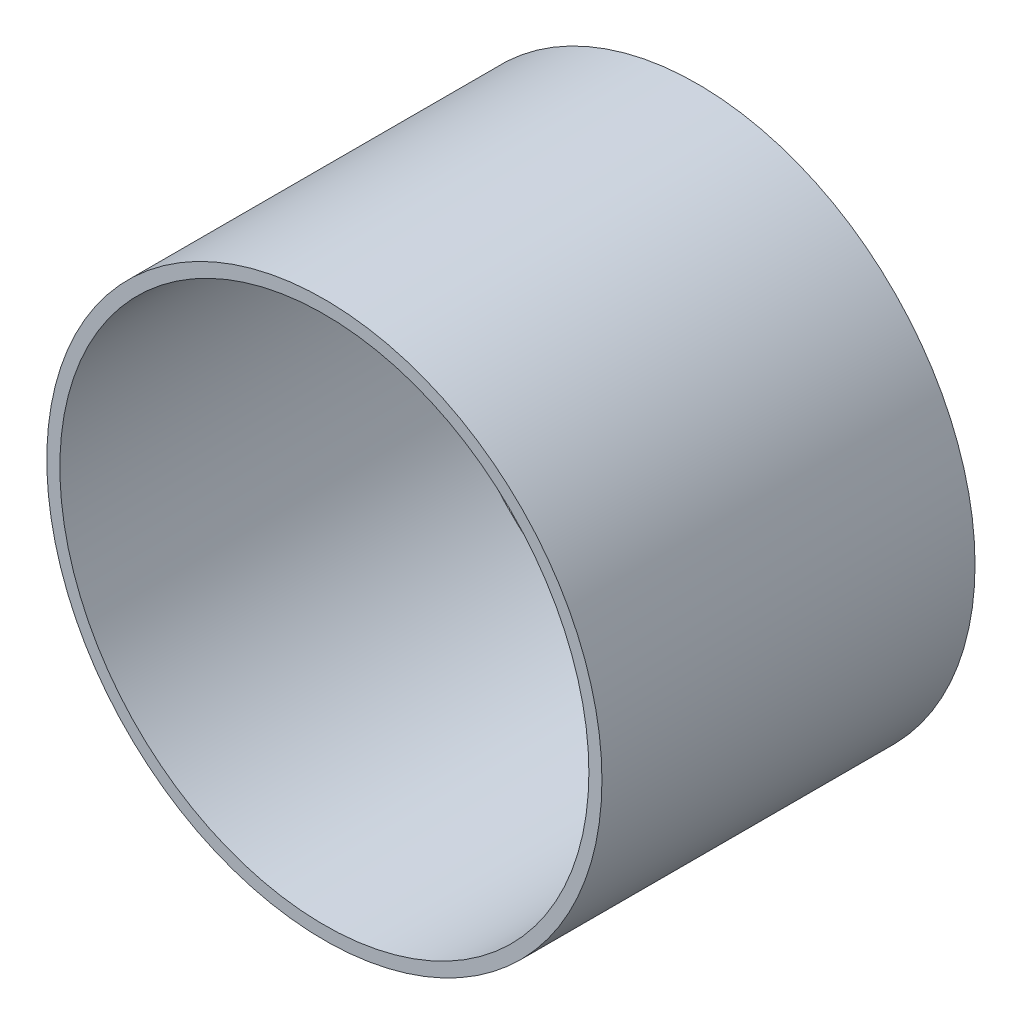
SolidWorks part; units mm, degrees
material "6061-T6 (SS)"
ref_plane "Front Plane" through (0, 0, 0) normal (0, 0, 1) x (1, 0, 0)
ref_plane "Top Plane" through (0, 0, 0) normal (0, 1, 0) x (1, 0, 0)
ref_plane "Right Plane" through (0, 0, 0) normal (1, 0, 0) x (0, 0, -1)
sketch "Sketch4" plane through (0, 0, 0) normal (1, 0, 0) x (0, 0, -1)
  line L0 (0, 0) -> (160.8624, 0) construction
  line L1 (0, 36.0172) -> (0, 37.7952)
  line L2 (0, 37.7952) -> (50.8, 37.7952)
  line L4 (50.8, 37.7952) -> (50.8, 36.0172)
  line L5 (50.8, 36.0172) -> (0, 36.0172)
  dimension "D1" = 1.778
  dimension "D2" = 75.5904
  dimension "D5" = 50.8
revolve "Revolve1" add sketch "Sketch4" angle 360 about L0
